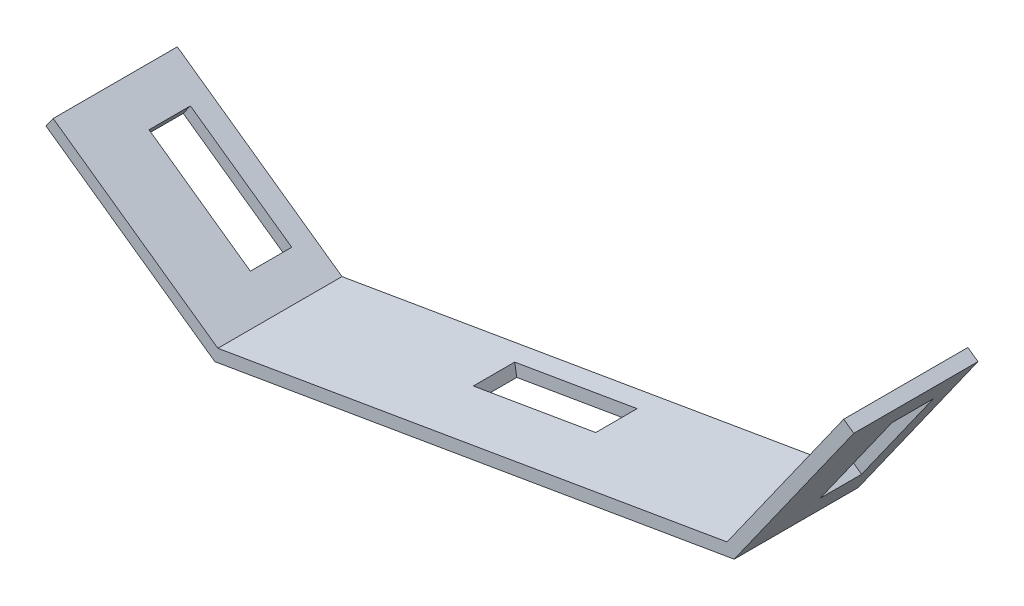
SolidWorks part; units mm, degrees
material "Acrylic (Medium-high impact)"
ref_plane "Front Plane" through (0, 0, 0) normal (0, 0, 1) x (1, 0, 0)
ref_plane "Top Plane" through (0, 0, 0) normal (0, 1, 0) x (1, 0, 0)
ref_plane "Right Plane" through (0, 0, 0) normal (1, 0, 0) x (0, 0, -1)
sketch "Sketch1" plane through (0, 0, 0) normal (0, 0, 1) x (1, 0, 0)
  line L0 (-52.842, 15.4027) -> (-12.0444, -13.5032)
  line L1 (-12.0444, -13.5032) -> (113.432, 7.9035)
  line L2 (113.432, 7.9035) -> (142.338, 48.7011)
  line L3 (-51.1076, 17.8506) -> (-11.3239, -10.337)
  line L4 (-11.3239, -10.337) -> (111.7026, 10.6518)
  line L5 (111.7026, 10.6518) -> (139.8901, 50.4355)
  line L6 (-52.842, 15.4027) -> (-51.1076, 17.8506)
  line L7 (139.8901, 50.4355) -> (142.338, 48.7011)
  dimension "D1" = 198
  dimension "D2" = 135
  dimension "D3" = 135
  dimension "D4" = 50
  dimension "D5" = 50
  dimension "D6" = 3
extrude "Boss-Extrude1" add sketch "Sketch1" along normal blind 30
sketch "Sketch4" plane through (1.8979, -11.1246, 0) normal (0.1682, -0.9858, 0) x (0.9858, 0.1682, 0)
  line L0 (-14.1437, 30) -> (113.1456, 30) construction
  line L1 (34.501, 15) -> (64.501, 15)
  line L2 (34.501, 15) -> (34.501, 5)
  line L3 (34.501, 5) -> (64.501, 5)
  line L4 (64.501, 15) -> (64.501, 5)
  line L5 (34.501, 15) -> (64.501, 5) construction
  line L6 (34.501, 5) -> (64.501, 15) construction
  point P0 (49.501, 10)
  point P7 (49.501, 30)
  point P10 (-5.4038, 44.1595)
  dimension "D1" = 10
  dimension "D2" = 30
  dimension "D3" = 0
  dimension "D4" = 20
extrude "Cut-Extrude1" cut sketch "Sketch4" against normal blind 22
sketch "Sketch5" plane through (-10.3952, -14.6717, 0) normal (-0.5781, -0.816, 0) x (0.816, -0.5781, 0)
  line L0 (-52.0212, 30) -> (-2.0212, 30) construction
  line L1 (-42.0212, 15) -> (-12.0212, 15)
  line L2 (-42.0212, 15) -> (-42.0212, 5)
  line L3 (-42.0212, 5) -> (-12.0212, 5)
  line L4 (-12.0212, 15) -> (-12.0212, 5)
  line L5 (-42.0212, 15) -> (-12.0212, 5) construction
  line L6 (-42.0212, 5) -> (-12.0212, 15) construction
  point P0 (-27.0212, 10)
  point P7 (-27.0212, 30)
  point P10 (-22.4947, 30)
  dimension "D1" = 30
  dimension "D2" = 10
  dimension "D3" = 0
  dimension "D4" = 20
extrude "Cut-Extrude2" cut sketch "Sketch5" against normal blind 22
sketch "Sketch7" plane through (71.7924, -50.8664, 0) normal (0.816, -0.5781, 0) x (0, 0, -1)
  line L0 (-30, 72.0261) -> (-30, 122.0261) construction
  line L1 (-15, 112.0261) -> (-5, 112.0261)
  line L2 (-15, 112.0261) -> (-15, 82.0261)
  line L3 (-15, 82.0261) -> (-5, 82.0261)
  line L4 (-5, 112.0261) -> (-5, 82.0261)
  line L5 (-15, 112.0261) -> (-5, 82.0261) construction
  line L6 (-15, 82.0261) -> (-5, 112.0261) construction
  point P0 (-10, 97.0261)
  point P7 (-30, 97.0261)
  dimension "D1" = 30
  dimension "D2" = 10
  dimension "D3" = 0
  dimension "D4" = 20
extrude "Cut-Extrude3" cut sketch "Sketch7" against normal blind 22
